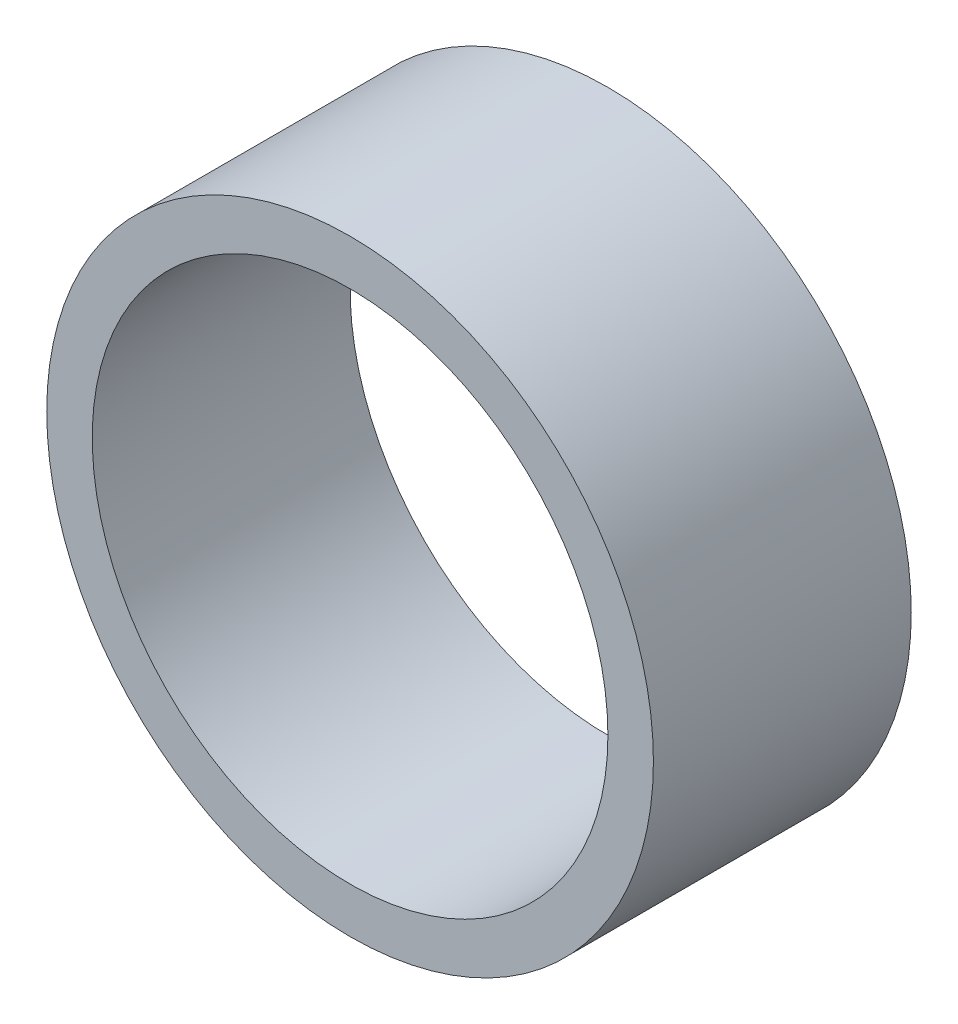
SolidWorks part; units mm, degrees
ref_plane "Piano frontale" through (0, 0, 0) normal (0, 0, 1) x (1, 0, 0)
ref_plane "Piano superiore" through (0, 0, 0) normal (0, 1, 0) x (1, 0, 0)
ref_plane "Piano destro" through (0, 0, 0) normal (1, 0, 0) x (0, 0, -1)
sketch "Schizzo1" plane through (0, 0, 0) normal (0, 0, 1) x (1, 0, 0)
  circle A0 centre (0, 0) radius 42.5
  circle A1 centre (0, 0) radius 50
  dimension "D1" = 85
  dimension "D2" = 100
extrude "Estrusione-Estrusione1" add sketch "Schizzo1" along normal blind 42.5
